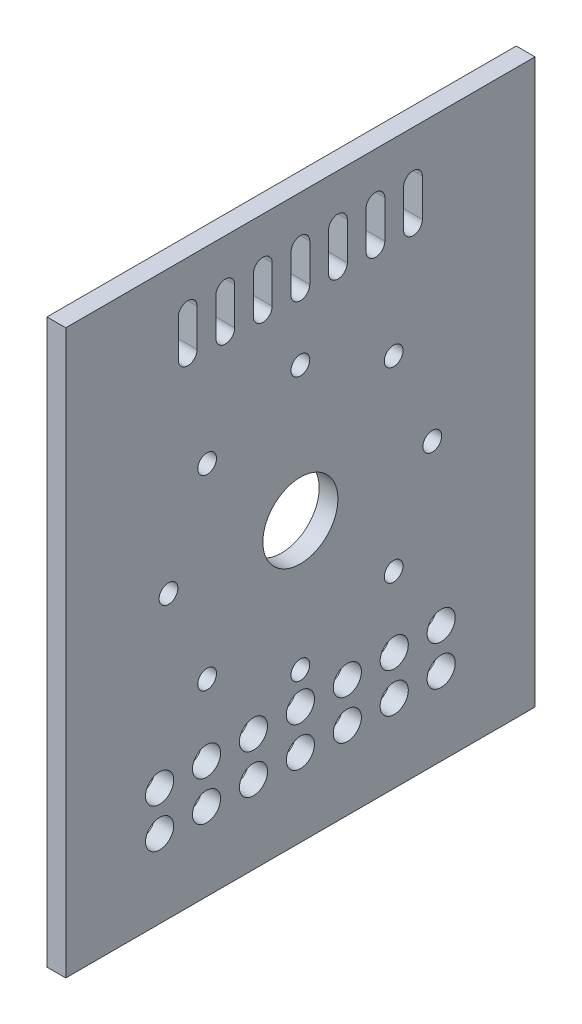
SolidWorks part; units mm, degrees
ref_plane "Front Plane" through (0, 0, 0) normal (0, 0, 1) x (1, 0, 0)
ref_plane "Top Plane" through (0, 0, 0) normal (0, 1, 0) x (1, 0, 0)
ref_plane "Right Plane" through (0, 0, 0) normal (1, 0, 0) x (0, 0, -1)
sketch "草图1" plane through (0, 0, 0) normal (1, 0, 0) x (0, 0, -1)
  line L0 (0, 147.148) -> (0, -150) construction
  line L1 (-125, 150) -> (125, 150)
  line L2 (-125, 150) -> (-125, -150)
  line L3 (-125, -150) -> (125, -150)
  line L4 (125, 150) -> (125, -150)
  line L5 (-125, 150) -> (125, -150) construction
  line L6 (-125, -150) -> (125, 150) construction
  line L7 (0, 125) -> (0, 105) construction
  line L8 (5, 125) -> (5, 105)
  line L9 (-5, 125) -> (-5, 105)
  line L10 (-125, 0) -> (125, 0) construction
  line L11 (20, 125) -> (20, 105) construction
  line L12 (25, 125) -> (25, 105)
  line L13 (15, 125) -> (15, 105)
  line L14 (40, 125) -> (40, 105) construction
  line L15 (45, 125) -> (45, 105)
  line L16 (35, 125) -> (35, 105)
  line L17 (60, 125) -> (60, 105) construction
  line L18 (65, 125) -> (65, 105)
  line L19 (55, 125) -> (55, 105)
  line L20 (-20, 125) -> (-20, 105) construction
  line L21 (-15, 125) -> (-15, 105)
  line L22 (-25, 125) -> (-25, 105)
  line L23 (-40, 125) -> (-40, 105) construction
  line L24 (-35, 125) -> (-35, 105)
  line L25 (-45, 125) -> (-45, 105)
  line L26 (-60, 125) -> (-60, 105) construction
  line L27 (-55, 125) -> (-55, 105)
  line L28 (-65, 125) -> (-65, 105)
  arc A0 (5, 125) -> (-5, 125) centre (0, 125) ccw
  arc A1 (-5, 105) -> (5, 105) centre (0, 105) ccw
  circle A3 centre (0, -1.426) radius 20
  circle A4 centre (0, 0) radius 70.265 construction
  circle A5 centre (0, -87.3668) radius 7.5
  circle A6 centre (0, 70.265) radius 5
  circle A7 centre (49.6849, 49.6849) radius 5
  circle A8 centre (0, 0) radius 70.265 construction
  circle A9 centre (70.265, 0) radius 5
  circle A10 centre (0, 0) radius 70.265 construction
  circle A11 centre (49.6849, -49.6849) radius 5
  circle A12 centre (0, 0) radius 70.265 construction
  circle A13 centre (0, -70.265) radius 5
  circle A14 centre (0, 0) radius 70.265 construction
  circle A15 centre (-49.6849, -49.6849) radius 5
  circle A16 centre (0, 0) radius 70.265 construction
  circle A17 centre (-70.265, 0) radius 5
  circle A18 centre (0, 0) radius 70.265 construction
  circle A19 centre (-49.6849, 49.6849) radius 5
  circle A20 centre (0, 0) radius 70.265 construction
  circle A21 centre (0, -108.4132) radius 7.5
  circle A22 centre (25, -87.3668) radius 7.5
  circle A23 centre (25, -108.4132) radius 7.5
  circle A24 centre (50, -87.3668) radius 7.5
  circle A25 centre (50, -108.4132) radius 7.5
  circle A26 centre (75, -87.3668) radius 7.5
  circle A27 centre (75, -108.4132) radius 7.5
  arc A28 (25, 125) -> (15, 125) centre (20, 125) ccw
  arc A29 (15, 105) -> (25, 105) centre (20, 105) ccw
  arc A30 (45, 125) -> (35, 125) centre (40, 125) ccw
  arc A31 (35, 105) -> (45, 105) centre (40, 105) ccw
  arc A32 (65, 125) -> (55, 125) centre (60, 125) ccw
  arc A33 (55, 105) -> (65, 105) centre (60, 105) ccw
  arc A42 (-15, 125) -> (-25, 125) centre (-20, 125) ccw
  arc A43 (-25, 105) -> (-15, 105) centre (-20, 105) ccw
  arc A46 (-35, 125) -> (-45, 125) centre (-40, 125) ccw
  arc A47 (-45, 105) -> (-35, 105) centre (-40, 105) ccw
  arc A50 (-55, 125) -> (-65, 125) centre (-60, 125) ccw
  arc A51 (-65, 105) -> (-55, 105) centre (-60, 105) ccw
  circle A52 centre (-25, -87.3668) radius 7.5
  circle A53 centre (-25, -108.4132) radius 7.5
  circle A54 centre (-50, -87.3668) radius 7.5
  circle A55 centre (-50, -108.4132) radius 7.5
  circle A56 centre (-75, -87.3668) radius 7.5
  circle A57 centre (-75, -108.4132) radius 7.5
  circle A58 centre (-20, -87.3668) radius 7.5 [skipped]
  circle A59 centre (-40, -87.3668) radius 7.5 [skipped]
  circle A60 centre (-60, -87.3668) radius 7.5 [skipped]
  circle A61 centre (-60, -108.4132) radius 7.5 [skipped]
  circle A62 centre (-40, -108.4132) radius 7.5 [skipped]
  circle A63 centre (-20, -108.4132) radius 7.5 [skipped]
  point P0 (0, 0)
  point P10 (0, 115)
  point P27 (5, 115)
  point P50 (0, 0)
  point P65 (20, 115)
  point P72 (40, 115)
  point P79 (60, 115)
  point P99 (-20, 115)
  point P110 (-40, 115)
  point P121 (-60, 115)
  dimension "D5" = 10
  dimension "D6" = 40
  dimension "D7" = 140.53
  dimension "D8" = 15
  dimension "D10" = 4
  dimension "D1" = 250
  dimension "D2" = 300
  dimension "D3" = 20
  dimension "D4" = 35
  dimension "D12" = 10
  dimension "D11" = 4
  dimension "D13" = 4
  dimension "D14" = 4
  dimension "D9" = 8
extrude "凸台-拉伸2" add sketch "草图1" along normal blind 10
